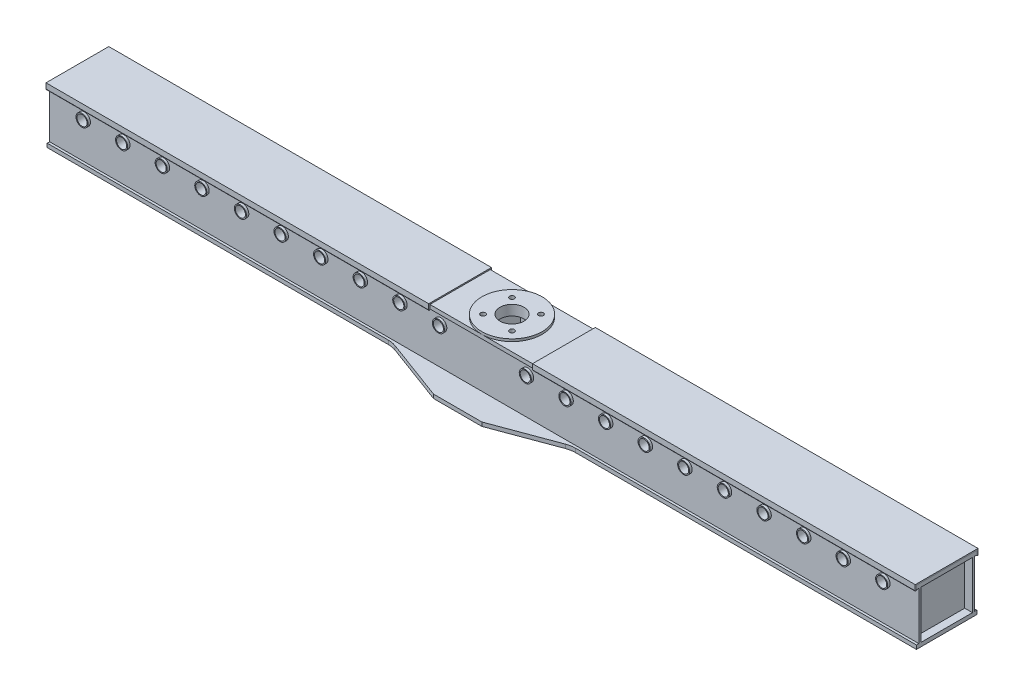
SolidWorks part; units mm, degrees
ref_plane "前视基准面" through (0, 0, 0) normal (0, 0, 1) x (1, 0, 0)
ref_plane "上视基准面" through (0, 0, 0) normal (0, 1, 0) x (1, 0, 0)
ref_plane "右视基准面" through (0, 0, 0) normal (1, 0, 0) x (0, 0, -1)
sketch "草图1" plane through (0, 0, 0) normal (0, 1, 0) x (1, 0, 0)
  line L0 (-1800, -125) -> (-1800, 125)
  line L1 (-1800, 125) -> (-387.4548, 125)
  line L2 (-100, 225) -> (-352.6667, 131.2461)
  line L3 (-100, 225) -> (100, 225)
  line L4 (352.6667, 131.2461) -> (100, 225)
  line L5 (387.4548, 125) -> (1800, 125)
  line L6 (1800, 125) -> (1800, -125)
  line L7 (1800, -125) -> (387.4548, -125)
  line L8 (-352.6667, -131.2461) -> (-100, -225)
  line L9 (100, -225) -> (-100, -225)
  line L10 (352.6667, -131.2461) -> (100, -225)
  line L11 (-387.4548, -125) -> (-1800, -125)
  line L12 (-1000, 0) -> (49000, 0) construction
  line L13 (0, -1000) -> (0, 49000) construction
  circle A0 centre (0, 0) radius 50
  arc A1 (-387.4548, 125) -> (-352.6667, 131.2461) centre (-387.4548, 225) ccw
  arc A2 (-352.6667, -131.2461) -> (-387.4548, -125) centre (-387.4548, -225) ccw
  arc A3 (387.4548, 125) -> (352.6667, 131.2461) centre (387.4548, 225) cw
  arc A4 (387.4548, -125) -> (352.6667, -131.2461) centre (387.4548, -225) ccw
  point P23 (-369.5, 125)
  point P26 (-369.5, -125)
  point P29 (369.5, 125)
  point P32 (369.5, -125)
  dimension "D6" = 100
  dimension "D7" = 100
  dimension "D8" = 100
  dimension "D9" = 100
  dimension "D10" = 100
  dimension "D1" = 3600
  dimension "D2" = 200
  dimension "D3" = 739
  dimension "D4" = 250
  dimension "D5" = 100
extrude "凸台-拉伸1" add sketch "草图1" along normal blind 16
sketch "草图2" plane through (0, 16, 0) normal (0, -1, 0) x (-1, 0, 0)
  line L0 (-1183.8164, -60) -> (48816.1836, -60) construction
  line L1 (1800, -125) -> (-1800, -125)
  line L2 (1800, -125) -> (1800, 125)
  line L3 (1800, 125) -> (-1800, 125)
  line L4 (-1800, -125) -> (-1800, 125)
  line L5 (-1203.8653, 60) -> (48796.1347, 60) construction
  line L6 (60, -992.1651) -> (60, 49007.8349) construction
  line L7 (-60, -972.1161) -> (-60, 49027.8839) construction
  circle A0 centre (0, 0) radius 50
  circle A1 centre (0, 0) radius 50 construction
  circle A2 centre (60, -60) radius 10
  circle A3 centre (-60, -60) radius 10
  circle A4 centre (60, 60) radius 10
  circle A5 centre (-60, 60) radius 10
  dimension "D5" = 20
  dimension "D1" = 60
  dimension "D2" = 60
  dimension "D3" = 60
  dimension "D4" = 60
extrude "凸台-拉伸2" add sketch "草图2" against normal blind 214
sketch "草图3" plane through (1800, 0, 0) normal (1, 0, 0) x (0, 0, -1)
  line L1 (-125, 230) -> (-125, 0) construction
  line L2 (-125, 214) -> (125, 214)
  line L3 (-125, 214) -> (-125, 16)
  line L4 (-125, 16) -> (125, 16)
  line L5 (125, 214) -> (125, 16)
  line L6 (125, 230) -> (125, 0) construction
  line L7 (131.2461, 16) -> (125, 16) construction
  line L8 (125, 230) -> (-125, 230) construction
  dimension "D1" = 16
extrude "切除-拉伸1" cut sketch "草图3" against normal through all
sketch "草图6" plane through (0, 214, 0) normal (0, -1, 0) x (1, 0, 0)
  line L1 (72, -107) -> (78, -107)
  line L2 (72, -107) -> (72, 107)
  line L3 (72, 107) -> (78, 107)
  line L4 (78, -107) -> (78, 107)
  dimension "D1" = 6
  dimension "D2" = 72
  dimension "D3" = 107
  dimension "D4" = 107
extrude "凸台-拉伸4" add sketch "草图6" along normal blind 198
pattern_linear "阵列(线性)2" count 2 spacing 150 along (1, 0, 0) of "凸台-拉伸4"
pattern_linear "阵列(线性)3" count 2 spacing 310 along (1, 0, 0) of "凸台-拉伸4"
pattern_linear "阵列(线性)4" count 2 spacing 500 along (1, 0, 0) of "凸台-拉伸4"
pattern_linear "阵列(线性)5" count 2 spacing 678 along (1, 0, 0) of "凸台-拉伸4"
pattern_linear "阵列(线性)6" count 2 spacing 855 along (1, 0, 0) of "凸台-拉伸4"
pattern_linear "阵列(线性)7" count 2 spacing 1055 along (1, 0, 0) of "凸台-拉伸4"
pattern_linear "阵列(线性)8" count 2 spacing 1290 along (1, 0, 0) of "凸台-拉伸4"
pattern_linear "阵列(线性)9" count 2 spacing 1490 along (1, 0, 0) of "凸台-拉伸4"
pattern_linear "阵列(线性)10" count 2 spacing 1690 along (1, 0, 0) of "凸台-拉伸4"
mirror "镜向2" about plane through (0, 0, 0) normal (1, 0, 0) of "阵列(线性)10", "阵列(线性)9", "阵列(线性)8", "阵列(线性)7", "阵列(线性)6", "阵列(线性)5", "阵列(线性)4", "阵列(线性)3", "阵列(线性)2", "凸台-拉伸4"
sketch "草图7" plane through (0, 214, 0) normal (0, -1, 0) x (1, 0, 0)
  line L0 (-1000, 0) -> (49000, 0) construction
  line L1 (0, -1000) -> (0, 49000) construction
  line L2 (-370, 10) -> (-370, -10)
  line L3 (-370, -10) -> (-228, -100)
  line L4 (-228, -100) -> (228, -100)
  line L5 (228, -100) -> (370, -10)
  line L6 (370, -10) -> (370, 10)
  line L7 (370, 10) -> (228, 100)
  line L8 (228, 100) -> (-228, 100)
  line L9 (-228, 100) -> (-370, 10)
  circle A0 centre (0, 0) radius 50
  circle A1 centre (0, 0) radius 50 construction
  circle A2 centre (-60, 60) radius 10
  circle A3 centre (60, 60) radius 10
  circle A4 centre (60, -60) radius 10
  circle A5 centre (-60, -60) radius 10
  circle A6 centre (-60, -60) radius 10 construction
  circle A7 centre (60, -60) radius 10 construction
  circle A8 centre (-60, 60) radius 10 construction
  circle A9 centre (60, 60) radius 10 construction
  dimension "D1" = 740
  dimension "D2" = 20
  dimension "D3" = 456
  dimension "D4" = 200
extrude "凸台-拉伸5" add sketch "草图7" along normal blind 16
sketch "草图8" plane through (228, 0, 0) normal (1, 0, 0) x (0, 0, -1)
  line L0 (107, 16) -> (107, 214) construction
  line L1 (-107, 214) -> (-100, 214)
  line L2 (-107, 214) -> (-107, 198)
  line L3 (-107, 198) -> (-100, 198)
  line L4 (-100, 214) -> (-100, 198)
  line L5 (100, 214) -> (107, 214)
  line L6 (100, 214) -> (100, 198)
  line L7 (100, 198) -> (107, 198)
  line L8 (107, 214) -> (107, 198)
  line L9 (100, 198) -> (-100, 198) construction
  line L10 (-107, 16) -> (-107, 214) construction
  line L11 (-100, 214) -> (-107, 214) construction
extrude "切除-拉伸3" cut sketch "草图8" against normal blind 444
sketch "草图4" plane through (1800, 0, 0) normal (1, 0, 0) x (0, 0, -1)
  line L0 (0, -1000) -> (0, 49000) construction
  line L1 (125, 214) -> (-125, 214) construction
  line L2 (-115, 214) -> (-107, 214)
  line L3 (-115, 214) -> (-115, 16)
  line L4 (-115, 16) -> (-107, 16)
  line L5 (-107, 214) -> (-107, 16)
  line L6 (-125, 16) -> (125, 16) construction
  line L8 (107, 214) -> (115, 214)
  line L9 (107, 214) -> (107, 16)
  line L10 (107, 16) -> (115, 16)
  line L11 (115, 214) -> (115, 16)
  dimension "D1" = 230
  dimension "D2" = 8
  dimension "D3" = 8
extrude "凸台-拉伸3" add sketch "草图4" against normal blind 3600
sketch "草图5" plane through (0, 0, 115) normal (0, 0, 1) x (1, 0, 0)
  line L0 (0, -1000) -> (0, 49000) construction
  line L1 (-1057.4528, 170) -> (48942.5472, 170) construction
  line L2 (-1800, 214) -> (1800, 214) construction
  circle A0 centre (-180, 170) radius 25
  dimension "D2" = 50
  dimension "D1" = 44
  dimension "D3" = 180
extrude "切除-拉伸2" cut sketch "草图5" against normal through all
sketch "草图11" plane through (0, 0, 125) normal (0, 0, 1) x (1, 0, 0)
  circle A0 centre (-180, 170) radius 21
  circle A1 centre (-180, 170) radius 25
  circle A2 centre (-180, 170) radius 25 construction
  dimension "D1" = 42
extrude "凸台-拉伸7" add sketch "草图11" against normal blind 250
pattern_linear "阵列(线性)1" count 10 spacing 164 along (-1, 0, 0) of "切除-拉伸2", "凸台-拉伸7"
mirror "镜向1" about plane through (0, 0, 0) normal (1, 0, 0) of "阵列(线性)1", "凸台-拉伸7", "切除-拉伸2"
sketch "草图9" plane through (0, 230, 0) normal (0, 1, 0) x (1, 0, 0)
  circle A0 centre (0, 0) radius 125
  circle A1 centre (0, 0) radius 50
  circle A2 centre (0, 0) radius 50 construction
  circle A3 centre (-60, 60) radius 10
  circle A4 centre (60, 60) radius 10
  circle A5 centre (-60, -60) radius 10
  circle A6 centre (60, -60) radius 10
  circle A7 centre (60, 60) radius 10 construction
  circle A8 centre (-60, 60) radius 10 construction
  circle A9 centre (-60, -60) radius 10 construction
  circle A10 centre (60, -60) radius 10 construction
  dimension "D1" = 250
extrude "凸台-拉伸6" add sketch "草图9" along normal blind 10
sketch "草图12" plane through (1800, 0, 0) normal (1, 0, 0) x (0, 0, -1)
  line L0 (-125, 214) -> (-125, 230)
  line L1 (-125, 230) -> (125, 230)
  line L2 (125, 230) -> (125, 214)
  line L3 (125, 214) -> (124.134, 212.5)
  line L4 (124.134, 212.5) -> (128.4641, 210)
  line L5 (128.4641, 210) -> (130, 212.6603)
  line L6 (130, 212.6603) -> (130, 235)
  line L7 (130, 235) -> (-130, 235)
  line L8 (-130, 235) -> (-130, 212.6603)
  line L9 (-130, 212.6603) -> (-128.4641, 210)
  line L10 (-128.4641, 210) -> (-124.134, 212.5)
  line L11 (-125, 214) -> (-124.134, 212.5)
  line L12 (-828.2694, 210) -> (49171.7306, 210) construction
  dimension "D1" = 5
  dimension "D2" = 5
  dimension "D3" = 5
  dimension "D4" = 20
  dimension "D5" = 5
  dimension "D6" = 5
  dimension "D7" = 2.5
  dimension "D8" = 2.5
extrude "凸台-拉伸8" add sketch "草图12" against normal blind 1585 separate body
sketch "草图13" plane through (-1800, 0, 0) normal (-1, 0, 0) x (0, 0, 1)
  line L0 (-125, 214) -> (-125, 230)
  line L1 (-125, 230) -> (125, 230)
  line L2 (125, 230) -> (125, 214)
  line L3 (125, 214) -> (124.134, 212.5)
  line L4 (124.134, 212.5) -> (128.4641, 210)
  line L5 (128.4641, 210) -> (130, 212.6603)
  line L6 (130, 212.6603) -> (130, 235)
  line L7 (130, 235) -> (-130, 235)
  line L8 (-130, 235) -> (-130, 212.6603)
  line L9 (-130, 212.6603) -> (-128.4641, 210)
  line L10 (-128.4641, 210) -> (-124.134, 212.5)
  line L11 (-124.134, 212.5) -> (-125, 214)
extrude "凸台-拉伸9" add sketch "草图13" against normal blind 1585 separate body
sketch "草图14" plane through (0, 0, 0) normal (0, -1, 0) x (-1, 0, 0)
  line L0 (-1000, 0) -> (49000, 0) construction
  line L1 (752.5, -1025.2413) -> (752.5, 48974.7587) construction
  line L2 (-752.5, -993.4315) -> (-752.5, 49006.5685) construction
  line L4 (877.5, -120) -> (627.5, -120)
  line L5 (877.5, -120) -> (877.5, 120)
  line L6 (877.5, 120) -> (627.5, 120)
  line L7 (627.5, -120) -> (627.5, 120)
  line L8 (-627.5, -120) -> (-877.5, -120)
  line L9 (-627.5, -120) -> (-627.5, 120)
  line L10 (-627.5, 120) -> (-877.5, 120)
  line L11 (-877.5, -120) -> (-877.5, 120)
  dimension "D1" = 752.5
  dimension "D2" = 752.5
  dimension "D3" = 125
  dimension "D4" = 125
  dimension "D5" = 120
  dimension "D6" = 120
  dimension "D7" = 125
  dimension "D8" = 125
  dimension "D9" = 120
  dimension "D10" = 120
extrude "凸台-拉伸10" add sketch "草图14" along normal blind 5
